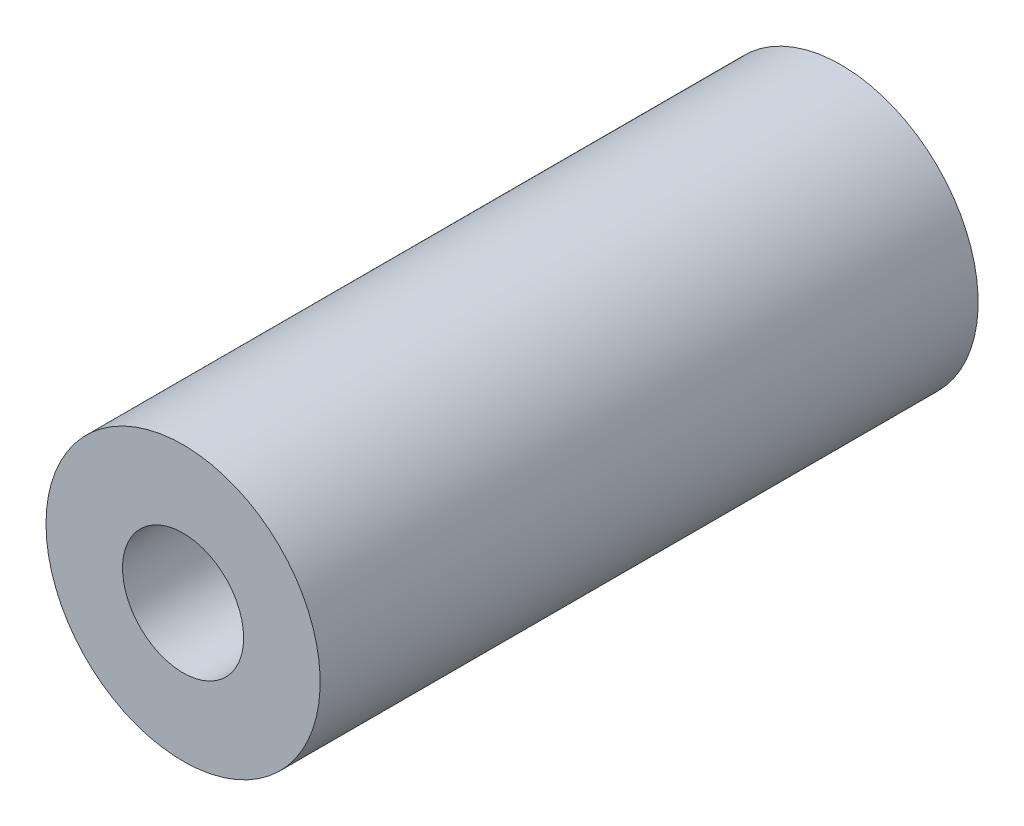
SolidWorks part; units mm, degrees
ref_plane "Front Plane" through (0, 0, 0) normal (0, 0, 1) x (1, 0, 0)
ref_plane "Top Plane" through (0, 0, 0) normal (0, 1, 0) x (1, 0, 0)
ref_plane "Right Plane" through (0, 0, 0) normal (1, 0, 0) x (0, 0, -1)
sketch "Sketch1" plane through (0, 0, 0) normal (0, 0, 1) x (1, 0, 0)
  circle A0 centre (0, 0) radius 3.9688
  dimension "D1" = 7.9375
extrude "Boss-Extrude1" add sketch "Sketch1" along normal mid plane 19.05
hole_wizard "#6-32 Tapped Hole1" positions "Sketch3" profile "Sketch2" tap size "#6-32" standard "ANSI Inch"
sketch "Sketch3" plane through (0, 0, -9.525) normal (0, 0, -1) x (-1, 0, 0)
  point P0 (0, 0)
sketch "Sketch2" plane through (0, 0, -9.525) normal (1, 0, 0) x (0, 1, 0)
  line L0 (0, 0) -> (0, 10.2107)
  line L1 (0, 10.2107) -> (1.3525, 9.398)
  line L2 (1.3525, 9.398) -> (1.3525, 7.112)
  line L3 (1.3525, 7.112) -> (1.7526, 7.112)
  line L4 (1.7526, 7.112) -> (1.7526, 0)
  line L5 (1.7526, 0) -> (0, 0)
  line L10 (0, 10.2107) -> (-1.3526, 9.398) construction
  line L11 (0, -6.35) -> (0, 107.95) construction
  dimension "Tap Drill Dia." = 2.7051
  dimension "Tap Drill Depth" = 9.398
  dimension "Thread Major Dia." = 3.5052
  dimension "Thread Depth" = 7.112
  dimension "Drill Angle" = 118
hole_wizard "#6-32 Tapped Hole2" positions "Sketch5" profile "Sketch4" tap size "#6-32" standard "ANSI Inch"
sketch "Sketch5" plane through (0, 0, 9.525) normal (0, 0, 1) x (1, 0, 0)
  point P0 (0, 0)
sketch "Sketch4" plane through (0, 0, 9.525) normal (1, 0, 0) x (0, -1, 0)
  line L0 (0, 0) -> (0, 10.2107)
  line L1 (0, 10.2107) -> (1.3525, 9.398)
  line L2 (1.3525, 9.398) -> (1.3525, 7.112)
  line L3 (1.3525, 7.112) -> (1.7526, 7.112)
  line L4 (1.7526, 7.112) -> (1.7526, 0)
  line L5 (1.7526, 0) -> (0, 0)
  line L10 (0, 10.2107) -> (-1.3526, 9.398) construction
  line L11 (0, -6.35) -> (0, 107.95) construction
  dimension "Tap Drill Dia." = 2.7051
  dimension "Tap Drill Depth" = 9.398
  dimension "Thread Major Dia." = 3.5052
  dimension "Thread Depth" = 7.112
  dimension "Drill Angle" = 118
